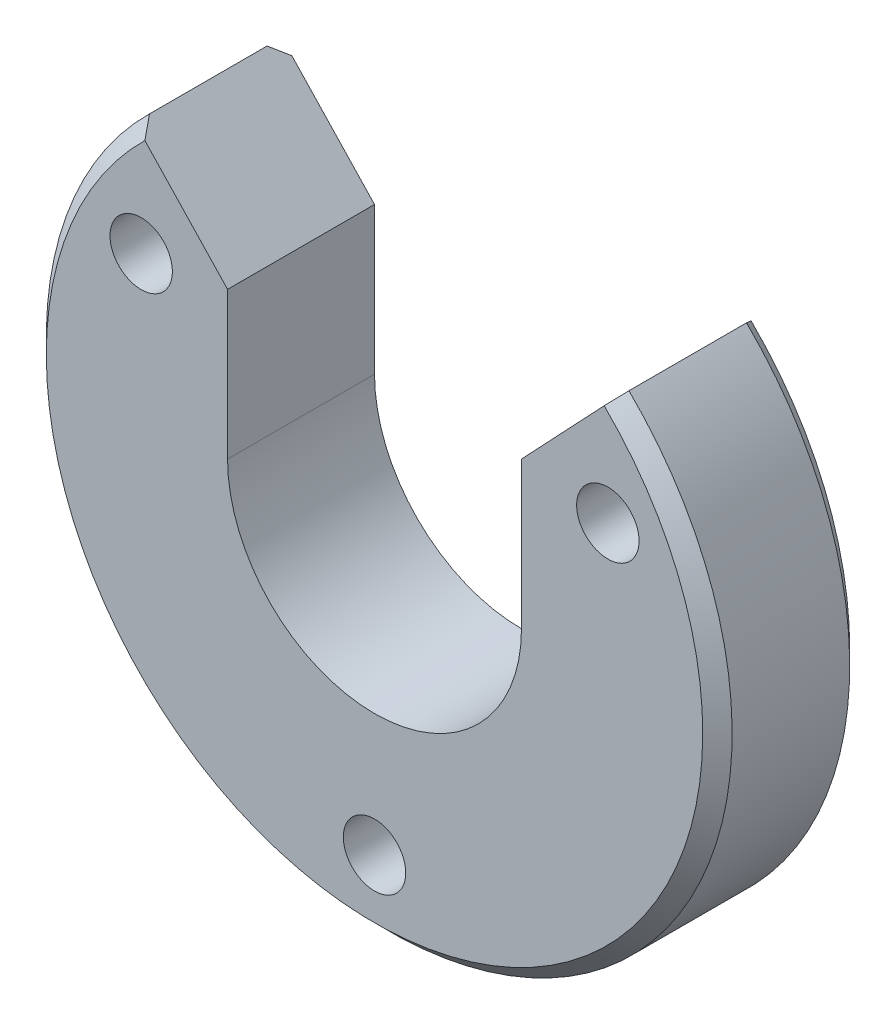
SolidWorks part; units mm, degrees
ref_plane "前基準面" through (0, 0, 0) normal (0, 0, 1) x (1, 0, 0)
ref_plane "上基準面" through (0, 0, 0) normal (0, 1, 0) x (1, 0, 0)
ref_plane "右基準面" through (0, 0, 0) normal (1, 0, 0) x (0, 0, -1)
sketch "草圖1" plane through (0, 0, 0) normal (0, 0, 1) x (1, 0, 0)
  circle A0 centre (0, 0) radius 6
  circle A1 centre (0, 0) radius 14
  dimension "D1" = 12
  dimension "D2" = 28
extrude "填料-伸長1" add sketch "草圖1" along normal blind 6
sketch "草圖2" plane through (0, 0, 6) normal (0, 0, 1) x (1, 0, 0)
  circle A0 centre (0, -11) radius 1.2738
  circle A1 centre (0, 0) radius 11 construction
  circle A2 centre (-9.5263, 5.5) radius 1.2738
  circle A3 centre (9.5263, 5.5) radius 1.2738
  point P11 (0, 0)
  dimension "D1" = 22
  dimension "D2" = 3
extrude "除料-伸長1" cut sketch "草圖2" against normal through all
sketch "草圖3" plane through (0, 0, 6) normal (0, 0, 1) x (1, 0, 0)
  line L0 (0, 0) -> (0, 14) construction
  line L1 (6, 0) -> (6, 6)
  line L2 (6, 6) -> (9.7877, 10.01)
  line L3 (-6, 6) -> (-9.7877, 10.01)
  line L4 (-6, 0) -> (-6, 6)
  line L5 (6, 0) -> (-6, 0)
  circle A0 centre (0, 0) radius 14 construction
  circle A1 centre (0, 0) radius 6 construction
  arc A2 (9.7877, 10.01) -> (-9.7877, 10.01) centre (0, 0) ccw
  dimension "D1" = 6
extrude "除料-伸長2" cut sketch "草圖3" against normal through all
chamfer "導角1" distance 0.6 angle 45 2 edges at (0, -14, 0) (0, -14, 6)
